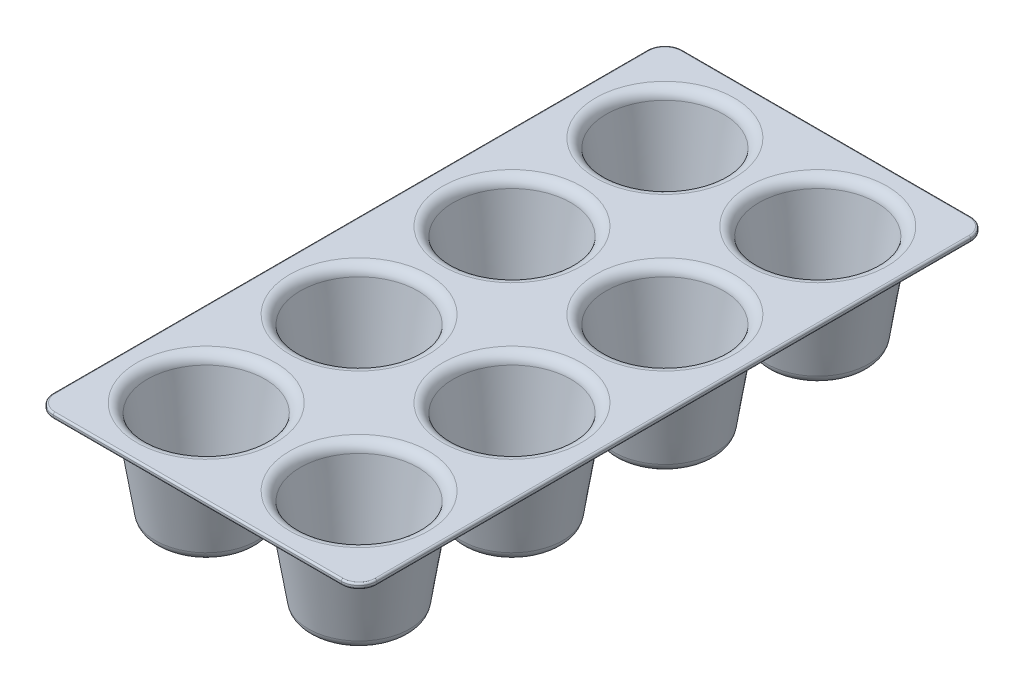
SolidWorks part; units mm, degrees
ref_plane "Front Plane" through (0, 0, 0) normal (0, 0, 1) x (1, 0, 0)
ref_plane "Top Plane" through (0, 0, 0) normal (0, 1, 0) x (1, 0, 0)
ref_plane "Right Plane" through (0, 0, 0) normal (1, 0, 0) x (0, 0, -1)
sketch "Sketch1" plane through (0, 0, 0) normal (0, 0, 1) x (1, 0, 0)
  line L0 (0, 5.8138) -> (0, -8.2461) construction
  line L1 (0, -33.193) -> (-22.6021, -33.193)
  line L2 (-28.5283, -28.1316) -> (-36.0369, 19.2764)
  line L3 (0, -30.193) -> (-22.6021, -30.193)
  line L4 (-25.5652, -27.6623) -> (-33.0739, 19.7457)
  line L5 (0, -30.193) -> (0, -33.193)
  line L6 (-39, 24.807) -> (-39, 21.807)
  arc A0 (-22.6021, -33.193) -> (-28.5283, -28.1316) centre (-22.6021, -27.193) cw
  arc A1 (-36.0369, 19.2764) -> (-39, 21.807) centre (-39, 18.807) ccw
  arc A2 (-22.6021, -30.193) -> (-25.5652, -27.6623) centre (-22.6021, -27.193) cw
  arc A3 (-33.0739, 19.7457) -> (-39, 24.807) centre (-39, 18.807) ccw
  dimension "D1" = 6
  dimension "D2" = 3
  dimension "D3" = 3
  dimension "D4" = 9
  dimension "D5" = 58
  dimension "D6" = 39
revolve "Revolve1" add sketch "Sketch1" angle 360 about L0
sketch "Sketch2" plane through (0, -33.193, 0) normal (0, -1, 0) x (-1, 0, 0)
  line L0 (0, 0) -> (0, -15.7713) construction
  line L1 (-8.8399, 0) -> (4.9222, 0) construction
pattern_linear "LPattern5" count 4 spacing 86 along (0, 0, 1) of bodies 101
pattern_linear "LPattern6" count 2 spacing 86 along (-1, 0, 0) of bodies 108 107 106 101
sketch "Sketch4" plane through (0, 0, 0) normal (1, 0, 0) x (0, 0, -1)
  line L0 (25.1484, 24.807) -> (86.3396, 24.807) construction
  line L2 (-39, 24.807) -> (39, 24.807) construction
ref_plane "Plane1" through (0, 24.807, 0) normal (0, -1, 0) x (0, 0, -1)
sketch "Sketch6" plane through (0, 24.807, 0) normal (0, -1, 0) x (0, 0, -1)
  line L0 (39, 0) -> (39, 35.4048) construction
  line L1 (38, 48) -> (-296, 48)
  line L2 (48, 38) -> (48, -124)
  line L3 (38, -134) -> (-296, -134)
  line L4 (-306, 38) -> (-306, -124)
  line L5 (0, 39) -> (-29.0687, 39) construction
  line L6 (-297, -86) -> (-297, -128.063) construction
  line L7 (-258, -125) -> (-222.6975, -125) construction
  circle A0 centre (0, 0) radius 39
  circle A1 centre (-86, 0) radius 39
  circle A2 centre (-172, 0) radius 39
  circle A3 centre (-258, 0) radius 39
  circle A4 centre (-86, -86) radius 39
  circle A5 centre (-172, -86) radius 39
  circle A6 centre (-258, -86) radius 39
  circle A7 centre (0, -86) radius 39
  arc A8 (-306, -124) -> (-296, -134) centre (-296, -124) ccw
  arc A9 (-306, 38) -> (-296, 48) centre (-296, 38) cw
  arc A10 (38, -134) -> (48, -124) centre (38, -124) ccw
  arc A11 (48, 38) -> (38, 48) centre (38, 38) ccw
  dimension "D3" = 78
  dimension "D8" = 10
  dimension "D9" = 10
  dimension "D10" = 10
  dimension "D11" = 10
  dimension "D4" = 9
  dimension "D5" = 9
  dimension "D6" = 9
  dimension "D7" = 9
  dimension "D1" = 4
  dimension "D2" = 2
extrude "Boss-Extrude2" add sketch "Sketch6" along normal blind 3
fillet "Fillet1" radius 1 8 edges at (-134, 24.807, 129) (-131.0711, 24.807, -45.0711) (-43, 24.807, -48) (45.0711, 24.807, -45.0711) (48, 24.807, 129) (45.0711, 24.807, 303.0711) (-43, 24.807, 306) (-131.0711, 24.807, 303.0711)
fillet "Fillet2" radius 1 8 edges at (-43, 21.807, 306) (45.0711, 21.807, 303.0711) (48, 21.807, 129) (45.0711, 21.807, -45.0711) (-43, 21.807, -48) (-131.0711, 21.807, -45.0711) (-134, 21.807, 129) (-131.0711, 21.807, 303.0711)
